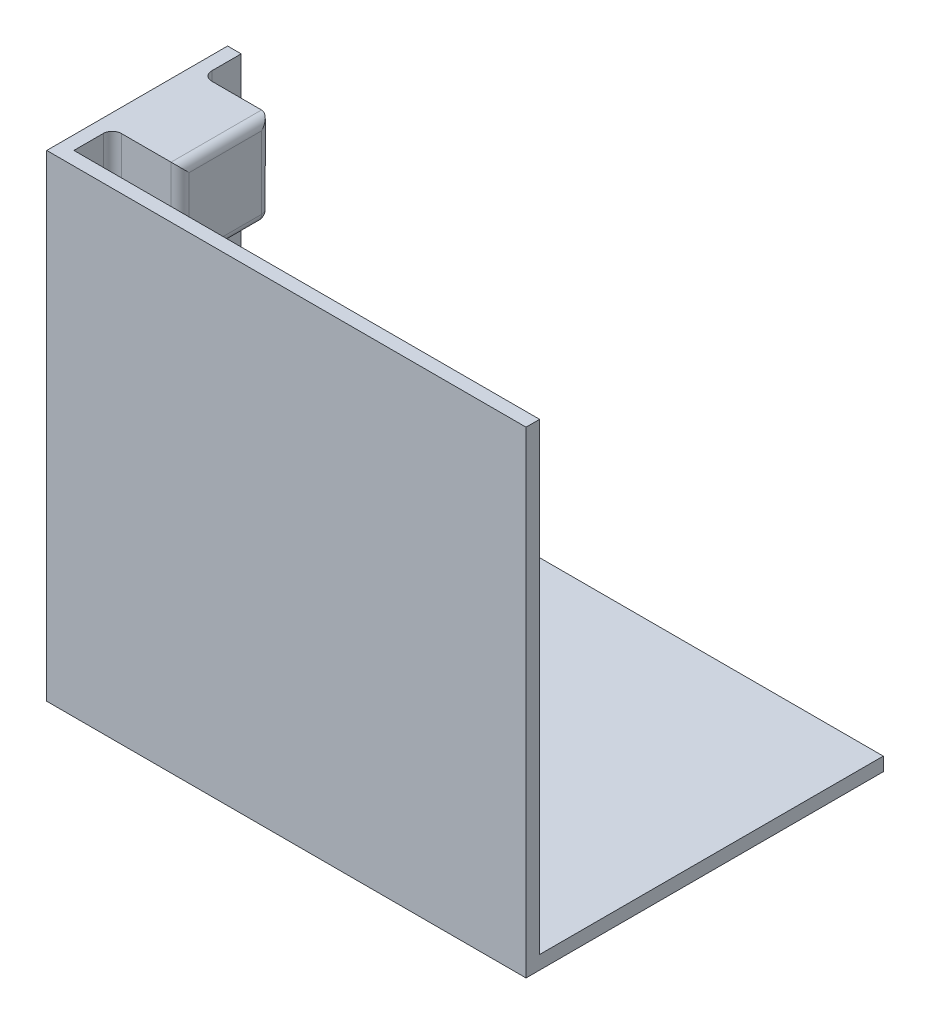
SolidWorks part; units mm, degrees
ref_plane "Front Plane" through (0, 0, 0) normal (0, 0, 1) x (1, 0, 0)
ref_plane "Top Plane" through (0, 0, 0) normal (0, 1, 0) x (1, 0, 0)
ref_plane "Right Plane" through (0, 0, 0) normal (1, 0, 0) x (0, 0, -1)
sketch "Sketch1" plane through (0, 0, 0) normal (0, 1, 0) x (1, 0, 0)
  line L1 (-50, -36.5) -> (50, -36.5)
  line L2 (-50, -36.5) -> (-50, 36.5)
  line L3 (-50, 36.5) -> (50, 36.5)
  line L4 (50, -36.5) -> (50, 36.5)
  line L5 (-50, -36.5) -> (50, 36.5) construction
  line L6 (-50, 36.5) -> (50, -36.5) construction
  point P0 (0, 0)
  dimension "D1" = 73
  dimension "D2" = 100
extrude "Boss-Extrude1" add sketch "Sketch1" along normal blind 3 contours L3 L4 L1 L2
sketch "Sketch2" plane through (0, 3, 0) normal (0, 1, 0) x (1, 0, 0)
  line L4 (-50, -36.5) -> (50, -36.5) construction
  line L5 (50, -36.5) -> (50, 36.5) construction
  line L6 (-50, 36.5) -> (50, 36.5) construction
  line L7 (-50, -36.5) -> (-50, 36.5) construction
  line L8 (-53, 39.5) -> (-53, -39.5)
  line L9 (-53, -39.5) -> (53, -39.5)
  line L10 (53, -39.5) -> (53, 39.5)
  line L11 (53, 39.5) -> (-53, 39.5)
  line L12 (-53, 39.5) -> (-53, -39.5)
  line L13 (-53, -39.5) -> (53, -39.5)
  line L14 (53, -39.5) -> (53, 39.5)
  line L15 (53, 39.5) -> (-53, 39.5)
  line L16 (-50, -36.5) -> (50, -36.5)
  line L17 (50, -36.5) -> (50, 36.5)
  line L18 (-50, 36.5) -> (50, 36.5)
  line L19 (-50, -36.5) -> (-50, 36.5)
  dimension "D1" = 3
extrude "Boss-Extrude2" add sketch "Sketch2" along normal blind 102.5 and the other way blind 3
sketch "Sketch3" plane through (0, 0, -39.5) normal (0, 0, -1) x (-1, 0, 0)
  line L1 (-53, 105.5) -> (53, 105.5)
  line L2 (-53, 105.5) -> (-53, 3)
  line L3 (-53, 3) -> (53, 3)
  line L4 (53, 105.5) -> (53, 3)
  line L5 (-53, 105.5) -> (53, 105.5) construction
  line L7 (-53, 0) -> (53, 0) construction
  line L9 (-53, 0) -> (-53, 105.5) construction
  point P6 (0, 105.5)
  dimension "D1" = 3
extrude "Cut-Extrude1" cut sketch "Sketch3" against normal blind 39
sketch "Sketch4" plane through (53, 0, 0) normal (1, 0, 0) x (0, 0, -1)
  line L0 (-39.5, 105.5) -> (0.5, 105.5) construction
  line L1 (-36.5, 105.5) -> (0.5, 105.5)
  line L2 (-36.5, 105.5) -> (-36.5, 3)
  line L3 (-36.5, 3) -> (0.5, 3)
  line L4 (0.5, 105.5) -> (0.5, 3)
  line L5 (-39.5, 0) -> (-39.5, 105.5) construction
  dimension "D1" = 3
extrude "Cut-Extrude2" cut sketch "Sketch4" against normal up to next
sketch "Sketch5" plane through (-50, 0, 0) normal (1, 0, 0) x (0, 0, -1)
  line L1 (-8, 105.5) -> (-28, 105.5)
  line L2 (-8, 105.5) -> (-8, 85.5)
  line L3 (-8, 85.5) -> (-28, 85.5)
  line L4 (-28, 105.5) -> (-28, 85.5)
  line L5 (-39.5, 105.5) -> (-36.5, 105.5) construction
  line L6 (0.5, 105.5) -> (-36.5, 105.5) construction
  point P5 (0, 0)
  point P8 (-18, 105.5)
  dimension "D1" = 20
  dimension "D2" = 20
extrude "Boss-Extrude3" add sketch "Sketch5" along normal blind 15
fillet "Fillet1" radius 2 9 edges at (-50, 85.5, 18) (-35, 85.5, 18) (-35, 105.5, 18) (-35, 95.5, 28) (-42.5, 85.5, 28) (-50, 95.5, 28) (-42.5, 85.5, 8) (-35, 95.5, 8) (-50, 95.5, 8)
